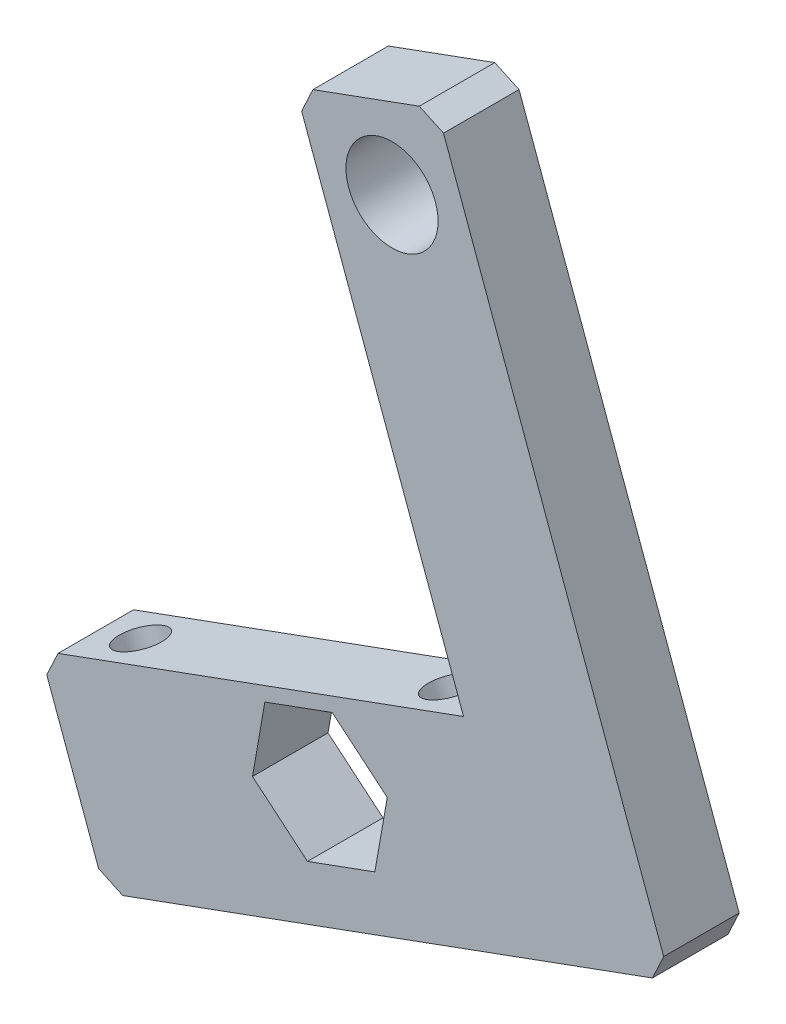
SolidWorks part; units mm, degrees
ref_plane "前基準面" through (0, 0, 0) normal (0, 0, 1) x (1, 0, 0)
ref_plane "上基準面" through (0, 0, 0) normal (0, 1, 0) x (1, 0, 0)
ref_plane "右基準面" through (0, 0, 0) normal (1, 0, 0) x (0, 0, -1)
sketch "草圖1" plane through (0, 0, 0) normal (0, 0, 1) x (1, 0, 0)
  line L0 (-29.9561, 9.7552) -> (-48.7426, 2.8947)
  line L2 (-48.7426, 2.8947) -> (-26.446, -58.1615)
  line L3 (-26.446, -58.1615) -> (-82.4902, -78.6278)
  line L4 (-82.4902, -78.6278) -> (-73.9146, -102.111)
  line L5 (-73.9146, -102.111) -> (0.9161, -74.7842)
  line L6 (0.9161, -74.7842) -> (-29.9561, 9.7552)
  circle A0 centre (-35.9191, -3.0683) radius 6.1
  dimension "D4" = 12.2
  dimension "D5" = 10
  dimension "D1" = 20
  dimension "D2" = 25
  dimension "D3" = 65
  dimension "D6" = 10
extrude "填料-伸長1" add sketch "草圖1" along normal blind 10
sketch "草圖2" plane through (15.6286, -42.7967, 0) normal (-0.343, 0.9393, 0) x (0.9393, 0.343, 0)
  circle A0 centre (-95.6715, -4.9822) radius 3
  circle A1 centre (-52.1263, -4.9822) radius 3
  dimension "D1" = 6
  dimension "D2" = 6
extrude "除料-伸長2" cut sketch "草圖2" against normal through all
chamfer "導角1" distance 2.5 angle 45 5 edges at (-29.9561, 9.7552, 5) (-48.7426, 2.8947, 5) (0.9161, -74.7842, 5) (-73.9146, -102.111, 5) (-82.4902, -78.6278, 5)
sketch "草圖3" plane through (0, 0, 0) normal (0, 0, -1) x (-1, 0, 0)
  line L0 (152.0261, -114.667) -> (6.0939, -61.3752) construction
  line L1 (47.1099, -85.1122) -> (43.8306, -66.3973) construction
  line L2 (52.7542, -69.6561) -> (38.1863, -81.8535) construction
  line L3 (54.3939, -79.0135) -> (36.5467, -72.496) construction
  line L10 (52.7542, -69.6561) -> (54.3939, -79.0135)
  line L13 (54.3939, -79.0135) -> (47.1099, -85.1122)
  line L14 (43.8306, -66.3973) -> (36.5467, -72.496)
  line L20 (36.5467, -72.496) -> (38.1863, -81.8535)
  line L21 (38.1863, -81.8535) -> (47.1099, -85.1122)
  line L22 (52.7542, -69.6561) -> (43.8306, -66.3973)
  line L23 (71.5663, -101.2534) -> (1.4322, -75.6418) construction
  circle A0 centre (45.4703, -75.7548) radius 5 construction
  point P2 (0, 0)
  point P5 (79.06, -88.0211)
  point P8 (45.4703, -75.7548)
  point P11 (45.4703, -75.7548)
  point P15 (45.4703, -75.7548)
  point P17 (45.4703, -75.7548)
  dimension "D1" = 60
  dimension "D2" = 60
extrude "除料-伸長3" cut sketch "草圖3" against normal through all
